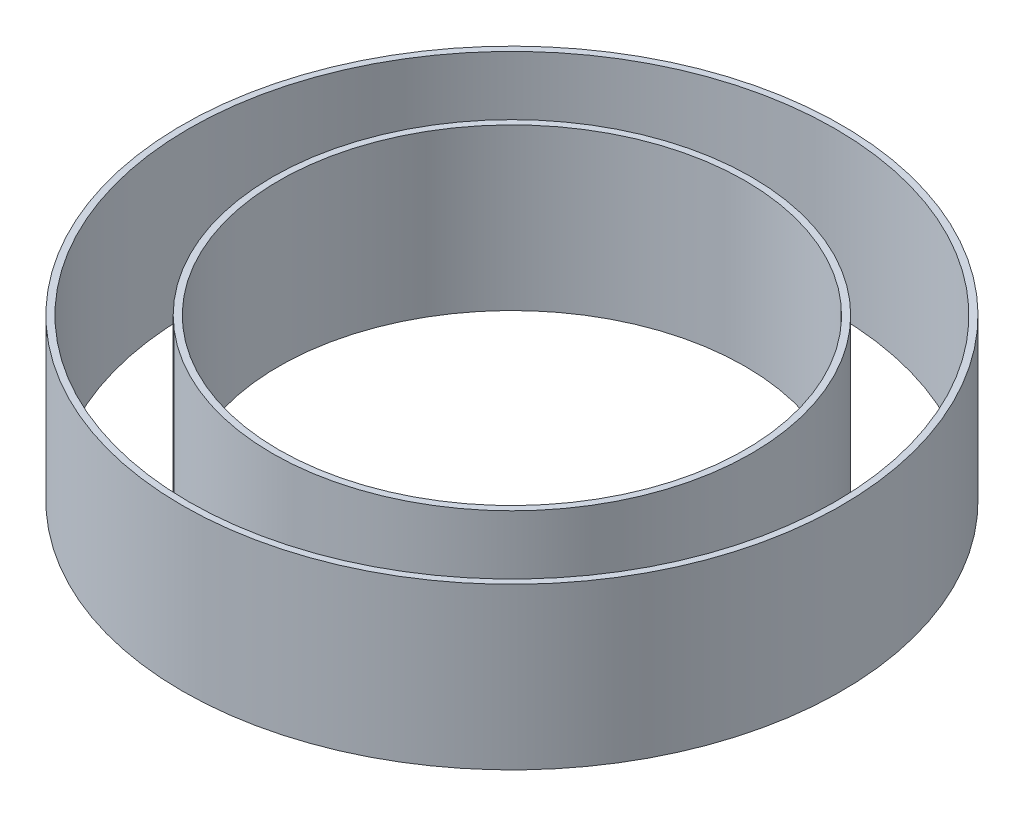
SolidWorks part; units mm, degrees
ref_plane "Front Plane" through (0, 0, 0) normal (0, 0, 1) x (1, 0, 0)
ref_plane "Top Plane" through (0, 0, 0) normal (0, 1, 0) x (1, 0, 0)
ref_plane "Right Plane" through (0, 0, 0) normal (1, 0, 0) x (0, 0, -1)
sketch "Sketch1" plane through (0, 0, 0) normal (0, 1, 0) x (1, 0, 0)
  circle A0 centre (0, 0) radius 20.5
  circle A1 centre (0, 0) radius 14.5
  circle A2 centre (0, 0) radius 14.9
  circle A3 centre (0, 0) radius 20.1
  dimension "D1" = 41
  dimension "D2" = 29
  dimension "D3" = 0.4
  dimension "D4" = 0.4
extrude "Boss-Extrude1" add sketch "Sketch1" along normal mid plane 10 contours A0 A3 | A1 | A2
